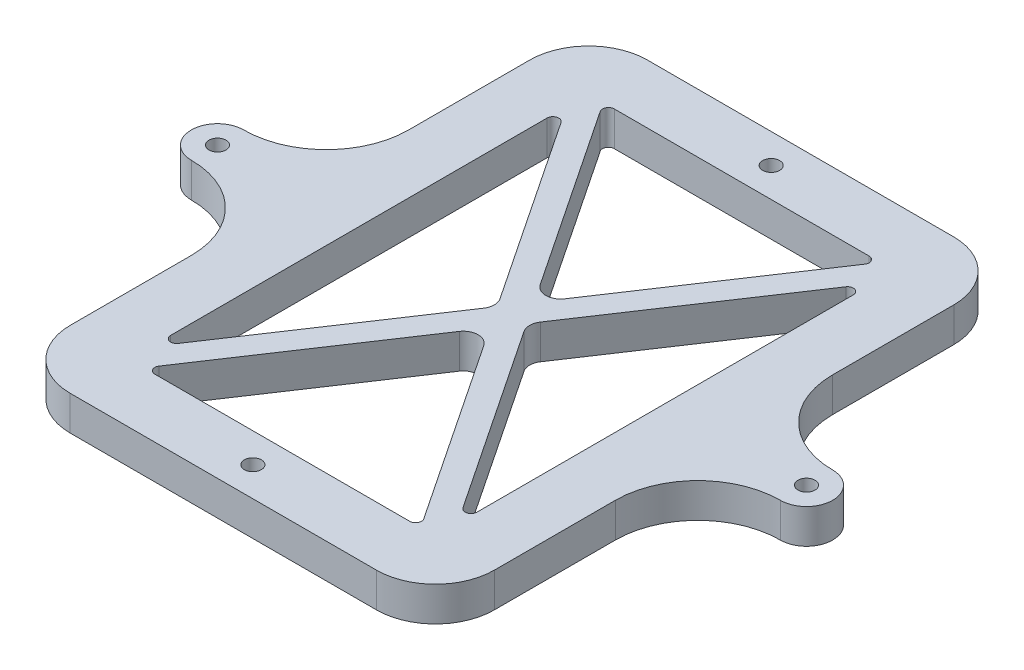
SolidWorks part; units mm, degrees
material "Acrylic (Medium-high impact)"
ref_plane "Front Plane" through (0, 0, 0) normal (0, 0, 1) x (1, 0, 0)
ref_plane "Top Plane" through (0, 0, 0) normal (0, 1, 0) x (1, 0, 0)
ref_plane "Right Plane" through (0, 0, 0) normal (1, 0, 0) x (0, 0, -1)
sketch "Sketch1" plane through (0, 0, 0) normal (0, 1, 0) x (1, 0, 0)
  line L0 (-36, 49) -> (-36, 18.45) construction
  line L1 (-36, 49) -> (36, 49) construction
  line L2 (-36, -49) -> (36, -49) construction
  line L3 (36, 49) -> (36, 18.45) construction
  line L4 (-28.5, -39) -> (-23.5, -39)
  line L5 (-28.5, -39) -> (23.5, 39)
  line L6 (-55, 0) -> (55, 0) construction
  line L7 (-74.55, 39) -> (-36, 39) construction
  line L8 (-26, 39) -> (26, 39)
  line L9 (-26, 39) -> (-26, -39)
  line L10 (-26, -39) -> (26, -39)
  line L11 (26, 39) -> (26, -39)
  line L12 (-26, 39) -> (26, -39) construction
  line L13 (-26, -39) -> (26, 39) construction
  line L14 (-71.5261, -39) -> (60.5097, -39) construction
  line L15 (-36, 39) -> (-36, 18.45)
  line L16 (-26, -996.6512) -> (-26, 49003.3488) construction
  line L17 (26, -1000) -> (26, 49000) construction
  line L18 (-26, 49) -> (26, 49)
  line L19 (36, 39) -> (36, 18.45)
  line L20 (-26, -49) -> (26, -49)
  line L21 (-62.4665, 0) -> (49937.5335, 0) construction
  line L22 (0, 0) -> (0, 50000) construction
  line L23 (-23.5, -39) -> (26, 35.25)
  line L24 (23.5, 39) -> (26, 39)
  line L25 (28.5, -39) -> (23.5, -39)
  line L26 (28.5, -39) -> (-23.5, 39)
  line L27 (23.5, -39) -> (-26, 35.25)
  line L28 (-23.5, 39) -> (-26, 39)
  line L29 (-36, -18.45) -> (-36, -49) construction
  line L30 (-36, -18.45) -> (-36, -39)
  line L31 (36, -18.45) -> (36, -49) construction
  line L32 (36, -18.45) -> (36, -39)
  line L33 (-26, 39) -> (26, 39) construction
  line L34 (36, 39) -> (60.5097, 39) construction
  arc A0 (-36, 39) -> (-26, 49) centre (-26, 39) cw
  arc A1 (26, 49) -> (36, 39) centre (26, 39) cw
  arc A2 (36, -39) -> (26, -49) centre (26, -39) cw
  arc A3 (-26, -49) -> (-36, -39) centre (-26, -39) cw
  circle A4 centre (0, 44) radius 1.45
  circle A5 centre (0, -44) radius 1.45
  circle A6 centre (-50, 0) radius 1.45
  circle A7 centre (50, 0) radius 1.45
  arc A8 (-50, -4.45) -> (-50, 4.45) centre (-50, 0) cw
  arc A9 (-50, 4.45) -> (-36, 18.45) centre (-50, 18.45) ccw
  arc A10 (-50, -4.45) -> (-36, -18.45) centre (-50, -18.45) cw
  arc A11 (50, -4.45) -> (50, 4.45) centre (50, 0) ccw
  arc A12 (50, -4.45) -> (36, -18.45) centre (50, -18.45) ccw
  arc A13 (50, 4.45) -> (36, 18.45) centre (50, 18.45) cw
  point P1 (0, 0)
  point P3 (0, 0)
  point P24 (26, 0)
  point P25 (36, 39)
  point P26 (36, -39)
  point P27 (-26, 49)
  point P28 (26, 49)
  point P34 (26, -49)
  point P35 (-26, -49)
  dimension "D7" = 2.9
  dimension "D8" = 2.5
  dimension "D10" = 50
  dimension "D11" = 2.9
  dimension "D5" = 44
  dimension "D9" = 3
  dimension "D1" = 98
  dimension "D2" = 72
  dimension "D3" = 78
  dimension "D4" = 52
extrude "Boss-Extrude1" add sketch "Sketch1" along normal blind 5.85 contours A3 L20 A2 L19 A1 L18 A0 L15 A7 A6 A5 A4 L28 L8 L24 L23 L11 L26 L25 L10 L4 L5 L9 L27 | L23 L27 L5 L9 L4 | L27 L5 L26 L8 L9 | L9 L28 L27 | L9 L5 L4 | L25 L26 L11 | L27 L10 L11 L26 L23 | L27 L23 L26 L5 | L26 L23 L11 L8 L5 | L24 L11 L23
fillet "Fillet1" radius 1 8 edges at (-26, 2.925, 35.25) (-23.5, 2.925, 39) (23.5, 2.925, 39) (26, 2.925, 35.25) (26, 2.925, -35.25) (23.5, 2.925, -39) (-26, 2.925, -35.25) (-23.5, 2.925, -39)
fillet "Fillet2" radius 2.5 4 edges at (2.5, 2.925, 0) (0, 2.925, 3.75) (0, 2.925, -3.75) (-2.5, 2.925, 0)
